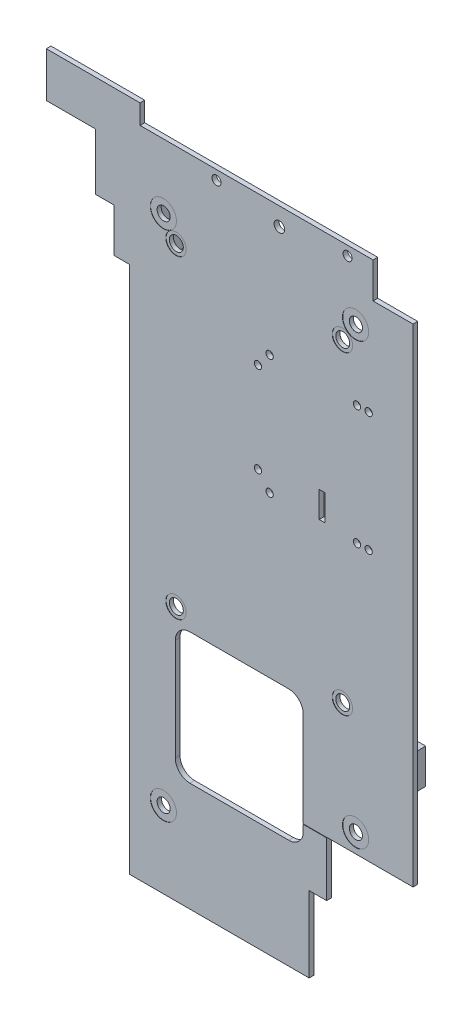
SolidWorks part; units mm, degrees
ref_plane "Plan de face" through (0, 0, 0) normal (0, 0, 1) x (1, 0, 0)
ref_plane "Plan de dessus" through (0, 0, 0) normal (0, 1, 0) x (1, 0, 0)
ref_plane "Plan de droite" through (0, 0, 0) normal (1, 0, 0) x (0, 0, -1)
sketch "Esquisse1" plane through (0, 0, 0) normal (0, 0, 1) x (1, 0, 0)
  line L0 (45.9025, -16.9999) -> (45.9025, -184.4154)
  line L1 (-47.83, 1.9148) -> (-80.0443, 1.9148)
  line L2 (-51.5124, -47.95) -> (-63.0976, -47.95)
  line L3 (32.17, -16.9999) -> (45.9025, -16.9999)
  line L4 (-63.0976, -13.5) -> (-63.0976, -47.95)
  line L5 (16.2209, -229.2964) -> (-51.5124, -229.2964)
  line L6 (-80.0443, -13.5) -> (-80.0443, 1.9148)
  line L7 (-62.3301, -57.95) -> (-60.8301, -57.95) construction
  line L8 (32.17, -16.9999) -> (32.17, -4.7964)
  line L10 (-63.0976, -13.5) -> (-80.0443, -13.5)
  line L11 (-51.5124, -229.2964) -> (-51.5124, -47.95)
  line L16 (32.17, -4.7964) -> (-47.83, -4.7964)
  line L17 (-47.83, 1.9148) -> (-47.83, -4.7964)
  line L41 (16.2209, -184.4154) -> (45.9025, -184.4154)
  line L42 (16.2209, -184.4154) -> (16.2209, -229.2964)
  dimension "D1" = 10
extrude "Extrusion1" add sketch "Esquisse1" along normal blind 1.6
sketch "Esquisse3" plane through (0, 0, 0) normal (0, 0, -1) x (-1, 0, 0)
  circle A0 centre (-21.6563, -141.7414) radius 2.4
  circle A1 centre (35.4937, -141.7414) radius 2.4
  circle A2 centre (-21.6563, -33.7914) radius 2.4
  circle A3 centre (35.4937, -33.7914) radius 2.4
extrude "Enlèv. mat.-Extru.2" cut sketch "Esquisse3" against normal blind 3
sketch "Esquisse4" plane through (0, 0, 1.6) normal (0, 0, 1) x (1, 0, 0)
  circle A0 centre (26.1701, -26.9998) radius 2.25
  circle A1 centre (-39.8299, -27.0002) radius 2.25
  circle A2 centre (26.1711, -177.9998) radius 2.25
  circle A3 centre (-39.8287, -203.0002) radius 2.25
extrude "Enlèv. mat.-Extru.3" cut sketch "Esquisse4" against normal blind 10
sketch "Esquisse5" plane through (0, 0, 0) normal (0, 0, -1) x (-1, 0, 0)
  line L4 (-8.1882, -186.8377) -> (-8.1882, -151.8378)
  line L5 (-3.1882, -146.8378) -> (30.7384, -146.8378)
  line L6 (35.7384, -151.8378) -> (35.7384, -186.8377)
  line L7 (30.7384, -191.8377) -> (-3.1882, -191.8377)
  arc A4 (-8.1882, -151.8378) -> (-3.1882, -146.8378) centre (-3.1882, -151.8378) cw
  arc A5 (35.7384, -151.8378) -> (30.7384, -146.8378) centre (30.7384, -151.8378) ccw
  arc A6 (30.7384, -191.8377) -> (35.7384, -186.8377) centre (30.7384, -186.8377) ccw
  arc A7 (-8.1882, -186.8377) -> (-3.1882, -191.8377) centre (-3.1882, -186.8377) ccw
  dimension "D4" = 5
extrude "Enlèv. mat.-Extru.4" cut sketch "Esquisse5" against normal blind 10
sketch "Esquisse6" plane through (0, 0, 1.6) normal (0, 0, 1) x (1, 0, 0)
  circle A0 centre (23.3999, -7.9999) radius 1.55
  circle A1 centre (-21.6001, -8) radius 1.55
extrude "Enlèv. mat.-Extru.5" cut sketch "Esquisse6" against normal blind 2
sketch "Esquisse7" plane through (0, 0, 1.6) normal (0, 0, 1) x (1, 0, 0)
  line L0 (27.3499, 0.0001) -> (24.5499, 0.0001) construction
  circle A0 centre (0, -10.9999) radius 1.8
  dimension "D1" = 11
extrude "Enlèv. mat.-Extru.6" cut sketch "Esquisse7" against normal blind 2
sketch "Esquisse8" plane through (0, 0, 0) normal (0, 0, -1) x (-1, 0, 0)
  line L0 (-45.9025, -184.4154) -> (-45.9025, -16.9999) construction
  line L1 (-44.1525, -146.4154) -> (-40.5525, -146.4154)
  line L2 (-16.2209, -184.4154) -> (-45.9025, -184.4154) construction
  line L3 (-44.1525, -158.4154) -> (-40.5525, -158.4154)
  line L4 (-40.5525, -146.4154) -> (-40.5525, -158.4154)
  line L7 (-44.1525, -146.4154) -> (-44.1525, -158.4154)
  dimension "D1" = 1.75
  dimension "D2" = 3.6
  dimension "D3" = 12
  dimension "D4" = 26
extrude "Extrusion2" add sketch "Esquisse8" along normal blind 4.5
sketch "Esquisse10" plane through (0, 0, 1.6) normal (0, 0, 1) x (1, 0, 0)
  circle A0 centre (26.17, -26.9999) radius 4.5
  circle A1 centre (-39.83, -27) radius 4.5
  circle A2 centre (26.1701, -177.9999) radius 4.5
  circle A3 centre (-39.8298, -203) radius 4.5
extrude "Enlèv. mat.-Extru.7" cut sketch "Esquisse10" against normal blind 0.1
sketch "Esquisse15" plane through (0, 0, 0) normal (0, 0, -1) x (-1, 0, 0)
  line L1 (-28.6525, -100.9164) -> (-28.6525, -77.7964)
  line L2 (-28.6525, -77.7964) -> (-42.0327, -77.7964)
  line L3 (-28.6525, -100.9164) -> (8.3475, -100.9164)
  line L5 (8.3475, -100.9164) -> (8.3475, -43.4865)
  line L6 (8.3475, -43.4865) -> (-42.0327, -43.4865)
  line L7 (-42.0327, -43.4865) -> (-42.0327, -77.7964)
extrude "Extrusion8" [suppressed] add sketch "Esquisse15" along normal blind 2
sketch "Esquisse22" plane through (0, 0, 0) normal (0, 0, -1) x (-1, 0, 0)
  line L0 (63.0976, -13.5) -> (63.0976, -47.95) construction
  line L1 (44.8476, -7.6369) -> (56.8476, -7.6369)
  line L2 (44.8476, -7.6369) -> (44.8476, -19.6369)
  line L3 (44.8476, -19.6369) -> (56.8476, -19.6369)
  line L4 (56.8476, -7.6369) -> (56.8476, -19.6369)
  dimension "D1" = 12
  dimension "D2" = 12
  dimension "D3" = 6.25
extrude "Extrusion13" [suppressed] add sketch "Esquisse22" along normal blind 8
sketch "Esquisse18" [suppressed] plane through (0, 0, 0) normal (0, 0, -1) x (-1, 0, 0)
  line L0 (8.3475, -100.9164) -> (8.3475, -43.4865) construction
  line L1 (10.3475, -88.3064) -> (48.8122, -88.3064)
  line L2 (10.3475, -88.3064) -> (10.3475, -47.95)
  line L4 (48.8122, -47.95) -> (48.8122, -88.3064)
  line L6 (48.8122, -47.95) -> (10.3475, -47.95)
  dimension "D1" = 2
  dimension "D2" = 2
extrude "Extrusion11" [suppressed] add sketch "Esquisse18" along normal blind 2
sketch "Esquisse19" plane through (0, 0, 0) normal (0, 0, -1) x (-1, 0, 0)
  line L0 (63.0976, -13.5) -> (63.0976, -47.95) construction
  line L1 (55.9476, -46.0347) -> (45.1476, -46.0347)
  line L2 (55.9476, -46.0347) -> (55.9476, -23.3347)
  line L3 (55.9476, -23.3347) -> (45.1476, -23.3347)
  line L4 (45.1476, -46.0347) -> (45.1476, -23.3347)
  dimension "D3" = 7.15
  dimension "D1" = 22.7
  dimension "D2" = 10.8
extrude "Extrusion12" add sketch "Esquisse19" along normal blind 13.2
sketch "Esquisse20" plane through (0, 0, 0) normal (0, 0, -1) x (-1, 0, 0)
  line L0 (-45.6524, -41.5408) -> (25.75, -41.5408)
  line L2 (25.75, -4.7964) -> (25.75, -41.5408)
  line L3 (25.75, -4.7964) -> (25.25, -4.7964)
  line L5 (-45.6524, -41.0408) -> (-45.6524, -41.5408)
  line L8 (25.25, -4.7964) -> (25.25, -41.0408)
  line L9 (-45.6524, -41.0408) -> (25.25, -41.0408)
  line L10 (-44.9945, -41.0408) -> (25.25, -41.0408) construction
  line L11 (-44.9945, -41.5408) -> (25.75, -41.5408) construction
  dimension "D1" = 0.5
extrude "Enlèv. mat.-Extru.8" [suppressed] cut sketch "Esquisse20" against normal blind 0.2
sketch "Esquisse21" plane through (0, 0, 1.6) normal (0, 0, 1) x (1, 0, 0)
  line L6 (-25.75, -41.5408) -> (45.6524, -41.5408)
  line L7 (-25.75, -4.7964) -> (-25.75, -41.5408)
  line L8 (-25.25, -4.7964) -> (-25.75, -4.7964)
  line L9 (-25.25, -41.0408) -> (-25.25, -4.7964)
  line L10 (45.6524, -41.0408) -> (-25.25, -41.0408)
  line L11 (45.6524, -41.5408) -> (45.6524, -41.0408)
  line L12 (-25.75, -41.5408) -> (45.6524, -41.5408)
  line L13 (-25.75, -4.7964) -> (-25.75, -41.5408)
  line L14 (-25.25, -4.7964) -> (-25.75, -4.7964)
  line L15 (-25.25, -41.0408) -> (-25.25, -4.7964)
  line L16 (45.6524, -41.0408) -> (-25.25, -41.0408)
  line L17 (45.6524, -41.5408) -> (45.6524, -41.0408)
  dimension "D1" = 0
extrude "Enlèv. mat.-Extru.9" [suppressed] cut sketch "Esquisse21" against normal blind 0.2
sketch "Esquisse23" plane through (0, 0, 1.6) normal (0, 0, 1) x (1, 0, 0)
  line L0 (16.2211, -184.4154) -> (8.1882, -184.4154)
  line L2 (16.2211, -184.6154) -> (8.1882, -184.6154)
  line L3 (8.1882, -184.6154) -> (8.1882, -184.4154)
  line L4 (22.2211, -184.6154) -> (8.1882, -184.6154) construction
  line L5 (16.2211, -184.6154) -> (16.2211, -184.4154)
  line L7 (22.2211, -184.4154) -> (8.1882, -184.4154) construction
extrude "Enlèv. mat.-Extru.10" cut sketch "Esquisse23" against normal blind 0.1
sketch "Esquisse26" plane through (0, 0, 0) normal (0, 0, -1) x (-1, 0, 0)
  circle A0 centre (-26.1711, -177.9998) radius 3.5
  circle A1 centre (-21.6563, -141.7414) radius 3.5
  circle A2 centre (35.4937, -141.7414) radius 3.5
  circle A3 centre (-26.1701, -26.9998) radius 3.5
  circle A4 centre (-21.6563, -33.7914) radius 3.5
  circle A5 centre (35.4937, -33.7914) radius 3.5
  circle A6 centre (39.8299, -27.0002) radius 3.5
extrude "Enlèv. mat.-Extru.11" cut sketch "Esquisse26" against normal blind 0.1
sketch "Esquisse27" plane through (0, 0, 1.6) normal (0, 0, 1) x (1, 0, 0)
  circle A0 centre (-35.4937, -33.7914) radius 3.5
  circle A1 centre (21.6563, -33.7914) radius 3.5
  circle A2 centre (-35.4937, -141.7414) radius 3.5
  circle A3 centre (21.6563, -141.7414) radius 3.5
extrude "Enlèv. mat.-Extru.12" cut sketch "Esquisse27" against normal blind 0.1
ref_plane "Plan1" through (0, 0, -10) normal (0, 0, -1) x (-1, 0, 0)
sketch "Esquisse30" plane through (0, 0, 0) normal (0, 0, -1) x (-1, 0, 0)
  line L1 (-16.2209, -184.4154) -> (-45.9025, -184.4154) construction
  circle A0 centre (-41.1525, -181.4154) radius 0.8
  dimension "D2" = 3
extrude "Extrusion14" add sketch "Esquisse30" along normal blind 1
sketch "Esquisse32" plane through (0, 0, 0) normal (0, 0, -1) x (-1, 0, 0)
  line L0 (-23.253, -203.2964) -> (-10.2209, -203.2964)
  line L1 (-16.2209, -229.2964) -> (-16.2209, -184.4154) construction
  line L2 (-10.2209, -203.2964) -> (-10.2209, -232.4158)
  line L3 (-23.253, -203.2964) -> (-23.253, -232.4158)
  line L4 (-23.253, -232.4158) -> (-10.2209, -232.4158)
  line L5 (51.5124, -229.2964) -> (-16.2209, -229.2964) construction
  dimension "D1" = 6
  dimension "D2" = 26
extrude "Enlèv. mat.-Extru.15" cut sketch "Esquisse32" against normal blind 10
sketch "Esquisse35" plane through (0, 0, 0) normal (0, 0, -1) x (-1, 0, 0)
  line L1 (-3.0209, -194.3268) -> (8.9791, -194.3268)
  line L2 (-3.0209, -194.3268) -> (-3.0209, -206.3268)
  line L3 (-3.0209, -206.3268) -> (8.9791, -206.3268)
  line L4 (8.9791, -194.3268) -> (8.9791, -206.3268)
  line L6 (-16.2209, -203.2964) -> (-16.2209, -184.4154) construction
  line L10 (51.5124, -229.2964) -> (-10.2209, -229.2964) construction
  dimension "D1" = 12
  dimension "D2" = 12
  dimension "D3" = 13.2
  dimension "D4" = 22.9696
extrude "Extrusion17" [suppressed] add sketch "Esquisse35" along normal blind 9.5
sketch "Esquisse38" plane through (0, 0, 0) normal (0, 0, -1) x (-1, 0, 0)
  line L1 (46.3306, -72.95) -> (49.8306, -72.95)
  line L2 (46.3306, -72.95) -> (46.3306, -81.95)
  line L3 (46.3306, -81.95) -> (49.8306, -81.95)
  line L4 (49.8306, -72.95) -> (49.8306, -81.95)
  line L5 (51.5124, -47.95) -> (51.5124, -229.2964) construction
  line L6 (63.0976, -47.95) -> (51.5124, -47.95) construction
  dimension "D1" = 3.5
  dimension "D2" = 9
  dimension "D3" = 25
  dimension "D4" = 1.6818
extrude "Extrusion20" add sketch "Esquisse38" along normal blind 5
sketch "Esquisse40" plane through (0, 0, 0) normal (0, 0, -1) x (-1, 0, 0)
  line L0 (-45.6524, -16.9999) -> (-69.1787, -16.9999) construction
  line L1 (-45.6524, -16.9999) -> (-45.6524, -3.6221) construction
  line L2 (-58.6412, -50.7999) -> (61.8299, -50.7999) construction
  line L3 (-30.6524, -44.8558) -> (-30.6524, -92.9817) construction
  line L4 (-26.6524, -44.8558) -> (-26.6524, -92.9817) construction
  line L5 (3.3476, -44.8558) -> (3.3476, -92.9817) construction
  line L6 (3.3476, -44.8558) -> (3.3476, -92.9817) construction
  line L7 (7.3476, -44.8558) -> (7.3476, -89.964) construction
  line L8 (-58.6412, -91.7999) -> (61.8299, -91.7999) construction
  line L9 (0.6973, -55.7999) -> (18.107, -55.7999) construction
  line L10 (0.6973, -86.7999) -> (18.107, -86.7999) construction
  line L11 (-15.6524, -82.2687) -> (-15.6524, -91.2342)
  line L12 (-13.6524, -82.2687) -> (-13.6524, -91.2342)
  line L13 (-15.6524, -82.2687) -> (-13.6524, -82.2687)
  line L14 (-15.6524, -91.2342) -> (-13.6524, -91.2342)
  circle A0 centre (-30.6524, -50.7999) radius 1.25
  circle A1 centre (-26.6524, -50.7999) radius 1.25
  circle A2 centre (3.3476, -50.7999) radius 1.25
  circle A3 centre (7.3476, -55.7999) radius 1.25
  circle A4 centre (-30.6524, -91.7999) radius 1.25
  circle A5 centre (-26.6524, -91.7999) radius 1.25
  circle A6 centre (3.3476, -91.7999) radius 1.25
  circle A7 centre (7.3476, -86.7999) radius 1.25
  dimension "D1" = 33.8
  dimension "D2" = 15
  dimension "D3" = 4
  dimension "D4" = 34
  dimension "D5" = 38
  dimension "D6" = 41
  dimension "D7" = 5
  dimension "D8" = 5
  dimension "D9" = 11
extrude "Enlèv. mat.-Extru.16" cut sketch "Esquisse40" against normal blind 10
sketch "Esquisse43" plane through (0, 0, 0) normal (0, 0, -1) x (-1, 0, 0)
  line L0 (56.8476, -52.1376) -> (56.8476, -32.95)
  line L1 (56.8476, -32.95) -> (73.0238, -32.95)
  line L3 (63.0976, -47.95) -> (51.5124, -47.95) construction
  line L4 (73.0238, -32.95) -> (73.0238, -52.1376)
  line L5 (73.0238, -52.1376) -> (56.8476, -52.1376)
  line L6 (63.0976, -13.5) -> (63.0976, -47.95) construction
  dimension "D1" = 6.25
  dimension "D2" = 15
extrude "Enlèv. mat.-Extru.17" cut sketch "Esquisse43" against normal blind 10
